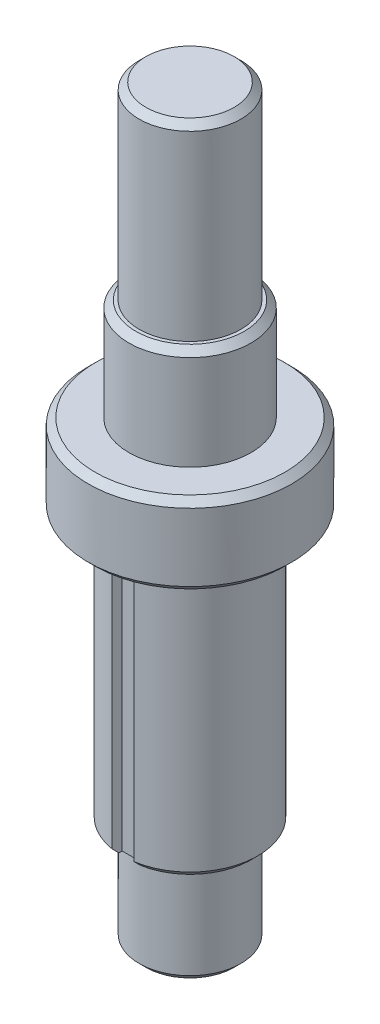
SolidWorks part; units mm, degrees
ref_plane "Front Plane" through (0, 0, 0) normal (0, 0, 1) x (1, 0, 0)
ref_plane "Top Plane" through (0, 0, 0) normal (0, 1, 0) x (1, 0, 0)
ref_plane "Right Plane" through (0, 0, 0) normal (1, 0, 0) x (0, 0, -1)
sketch "Sketch1" plane through (0, 0, 0) normal (0, 0, 1) x (1, 0, 0)
  line L0 (0, 0) -> (7.5, 0)
  line L1 (7.5, 0) -> (7.5, 15)
  line L2 (7.5, 15) -> (10, 15)
  line L3 (10, 15) -> (10, 55)
  line L4 (10, 55) -> (15, 55)
  line L5 (15, 55) -> (15, 67)
  line L6 (15, 67) -> (9, 67)
  line L7 (9, 67) -> (9, 82)
  line L8 (9, 82) -> (7.5, 82)
  line L9 (7.5, 82) -> (7.5, 109.85)
  line L10 (7.5, 109.85) -> (0, 109.85)
  line L11 (0, 109.85) -> (0, 0)
  line L12 (10, 35) -> (54.7446, 35) construction
  dimension "D1" = 7.5
  dimension "D2" = 10
  dimension "D3" = 15
  dimension "D4" = 40
  dimension "D5" = 15
  dimension "D6" = 12
  dimension "D7" = 15
  dimension "D8" = 74.85
  dimension "D9" = 9
revolve "Revolve1" add sketch "Sketch1" angle 360 about L11
sketch "Sketch2" plane through (0, 15, 0) normal (0, -1, 0) x (1, 0, 0)
  line L1 (-1.625, 11.625) -> (1.625, 11.625)
  line L2 (-1.625, 11.625) -> (-1.625, 8.375)
  line L3 (-1.625, 8.375) -> (1.625, 8.375)
  line L4 (1.625, 11.625) -> (1.625, 8.375)
  line L5 (-1.625, 11.625) -> (1.625, 8.375) construction
  line L6 (-1.625, 8.375) -> (1.625, 11.625) construction
  circle A0 centre (0, 0) radius 10 construction
  point P0 (0, 10)
  dimension "D1" = 3.25
extrude "Cut-Extrude1" cut sketch "Sketch2" against normal up to surface (40 mm away) up to face at (-15, 55, 0)
chamfer "Chamfer1" distance 1 angle 45 6 edges at (-7.5, 109.85, 0) (-7.5, 0, 0) (-15, 67, 0) (-15, 55, 0) (-9, 82, 0) (0, 15, -10)
sketch "Sketch3" plane through (0, 82, 0) normal (0, 1, 0) x (1, 0, 0)
  line L5 (-1.625, 10.625) -> (1.625, 10.625)
  line L6 (-1.625, 10.625) -> (-1.625, 7.375)
  line L7 (-1.625, 7.375) -> (1.625, 7.375)
  line L8 (1.625, 10.625) -> (1.625, 7.375)
  line L9 (-1.625, 10.625) -> (1.625, 7.375) construction
  line L10 (-1.625, 7.375) -> (1.625, 10.625) construction
  circle A1 centre (0, 0) radius 9 construction
  circle A2 centre (0, 0) radius 9 construction
  point P0 (0, 9)
  dimension "D1" = 3.25
extrude "Cut-Extrude2" cut sketch "Sketch3" against normal up to surface (15 mm away) up to face at (14, 67, 0)
